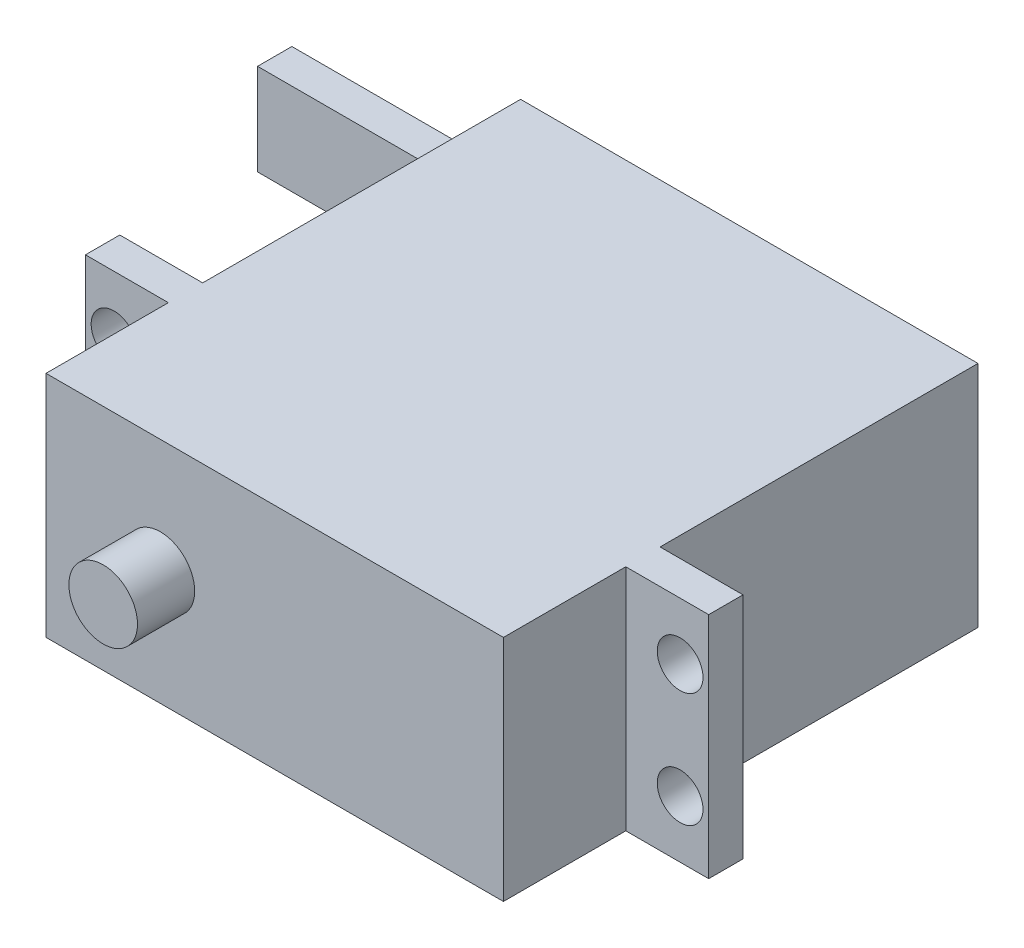
SolidWorks part; units mm, degrees
ref_plane "Top Plane" through (0, 0, 0) normal (0, 0, 1) x (1, 0, 0)
ref_plane "Right Plane" through (0, 0, 0) normal (0, 1, 0) x (1, 0, 0)
ref_plane "Front Plane" through (0, 0, 0) normal (1, 0, 0) x (0, 0, -1)
sketch "Sketch1" plane through (0, 0, 0) normal (0, 0, 1) x (1, 0, 0)
  line L0 (-10, 0) -> (30, 0) construction
  line L1 (-10, 10) -> (30, 10) construction
  line L2 (-10, 10) -> (-10, -10) construction
  line L3 (-10, -10) -> (30, -10) construction
  line L4 (30, 10) -> (30, -10) construction
  line L5 (-10, 10) -> (-17.25, 10) construction
  line L6 (-17.25, 10) -> (-17.25, -10) construction
  line L7 (-17.25, -10) -> (-10, -10) construction
  line L8 (10, 10) -> (10, -10) construction
  line L9 (37.25, -10) -> (30, -10) construction
  line L10 (37.25, 10) -> (37.25, -10) construction
  line L11 (30, 10) -> (37.25, 10) construction
  line L12 (0, -10) -> (0, 10) construction
  circle A0 centre (0, 0) radius 10 construction
  circle A1 centre (-14.75, 5) radius 2 construction
  circle A2 centre (-14.75, -5) radius 2 construction
  circle A3 centre (34.75, -5) radius 2 construction
  circle A4 centre (34.75, 5) radius 2 construction
  circle A5 centre (0, 0) radius 3
  dimension "D1" = 54.5
  dimension "D2" = 49.5
  dimension "D6" = 4
  dimension "D8" = 20
  dimension "D9" = 6
  dimension "D3" = 20
  dimension "D4" = 40
  dimension "D5" = 10
  dimension "D7" = 17.25
extrude "Boss-Extrude1" add sketch "Sketch1" against normal mid plane 5
sketch "Sketch2" plane through (0, 0, -2.5) normal (0, 0, -1) x (-1, 0, 0)
  line L1 (-30, 10) -> (10, 10)
  line L2 (-30, 10) -> (-30, -10)
  line L3 (-30, -10) -> (10, -10)
  line L4 (10, 10) -> (10, -10)
extrude "Boss-Extrude2" add sketch "Sketch2" along normal blind 41.5
sketch "Sketch3" plane through (0, 0, -44) normal (0, 0, -1) x (-1, 0, 0)
  line L1 (-37.25, 10) -> (-30, 10)
  line L2 (-37.25, 10) -> (-37.25, -10)
  line L3 (-37.25, -10) -> (-30, -10)
  line L4 (-30, 10) -> (-30, -10)
  line L5 (10, 10) -> (17.25, 10)
  line L6 (10, 10) -> (10, -10)
  line L7 (10, -10) -> (17.25, -10)
  line L8 (17.25, 10) -> (17.25, -10)
extrude "Boss-Extrude3" add sketch "Sketch3" against normal blind 3 from offset 27.8 offset against normal yes
sketch "Sketch4" plane through (0, 0, -13.2) normal (0, 0, 1) x (1, 0, 0)
  circle A0 centre (-14.75, -5) radius 2 construction
  circle A1 centre (-14.75, 5) radius 2 construction
  circle A2 centre (34.75, 5) radius 2 construction
  circle A3 centre (34.75, -5) radius 2 construction
  circle A4 centre (-14.75, -5) radius 2
  circle A5 centre (-14.75, 5) radius 2
  circle A6 centre (34.75, 5) radius 2
  circle A7 centre (34.75, -5) radius 2
extrude "Cut-Extrude1" cut sketch "Sketch4" against normal through all
sketch "Sketch5" plane through (-10, 0, 0) normal (-1, 0, 0) x (0, 0, 1)
  line L0 (-44, -10) -> (-44, 10) construction
  line L1 (-44, 4) -> (-41, 4)
  line L2 (-44, 4) -> (-44, -4)
  line L3 (-44, -4) -> (-41, -4)
  line L4 (-41, 4) -> (-41, -4)
  line L5 (-44, 0) -> (0, 0) construction
  line L6 (0, 10) -> (0, -10) construction
  dimension "D1" = 8
  dimension "D2" = 3
extrude "Boss-Extrude4" add sketch "Sketch5" along normal blind 20
sketch "Sketch6" plane through (0, 0, 0) normal (1, 0, 0) x (0, 0, -1)
  line L0 (-32.4992, 0) -> (61.7, 0) construction
